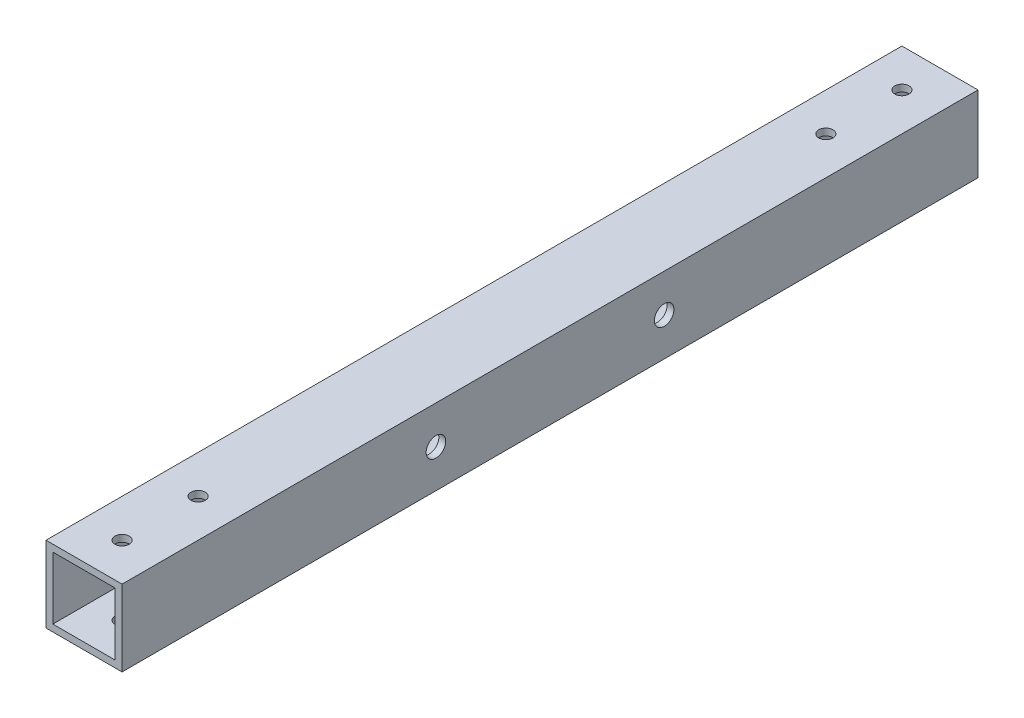
SolidWorks part; units mm, degrees
ref_plane "Front Plane" through (0, 0, 0) normal (0, 0, 1) x (1, 0, 0)
ref_plane "Top Plane" through (0, 0, 0) normal (0, 1, 0) x (1, 0, 0)
ref_plane "Right Plane" through (0, 0, 0) normal (1, 0, 0) x (0, 0, -1)
sketch "Sketch1" plane through (0, 0, 0) normal (0, 0, 1) x (1, 0, 0)
  line L0 (10.414, 10.414) -> (-10.414, 10.414)
  line L1 (12.7, -12.7) -> (-12.7, -12.7)
  line L2 (12.7, -12.7) -> (12.7, 12.7)
  line L3 (12.7, 12.7) -> (-12.7, 12.7)
  line L4 (-12.7, -12.7) -> (-12.7, 12.7)
  line L5 (12.7, -12.7) -> (-12.7, 12.7) construction
  line L6 (12.7, 12.7) -> (-12.7, -12.7) construction
  line L7 (-10.414, -10.414) -> (-10.414, 10.414)
  line L8 (10.414, -10.414) -> (-10.414, -10.414)
  line L9 (10.414, -10.414) -> (10.414, 10.414)
  point P0 (0, 0)
  dimension "D1" = 25.4
  dimension "D2" = 25.4
  dimension "D3" = 2.286
extrude "Boss-Extrude1" add sketch "Sketch1" along normal blind 285.75
hole_wizard "3/16 (0.1875) Diameter Hole7" positions "Sketch3" profile "Sketch2" hole size "3/16" standard "ANSI Inch" end condition through all
sketch "Sketch3" plane through (0, 12.7, 0) normal (0, 1, 0) x (1, 0, 0)
  line L0 (12.7, 0) -> (-12.7, 0) construction
  line L1 (12.7, -285.75) -> (-12.7, -285.75) construction
  point P0 (0, -273.05)
  point P2 (0, -247.65)
  point P3 (0, -12.7)
  point P5 (0, -38.1)
  dimension "D1" = 12.7
  dimension "D2" = 38.1
  dimension "D3" = 12.7
  dimension "D4" = 38.1
sketch "Sketch2" plane through (0, 12.7, 273.05) normal (1, 0, 0) x (0, 0, 1)
  line L0 (0, 0) -> (0, 25.4)
  line L1 (0, 25.4) -> (2.3812, 25.4)
  line L2 (2.3812, 25.4) -> (2.3812, 0)
  line L5 (2.3812, 0) -> (0, 0)
  line L11 (0, -6.35) -> (0, 107.95) construction
  dimension "Thru Hole Dia." = 4.7625
  dimension "Thru Hole Depth" = 25.4
hole_wizard " (0.257) Diameter Hole2" [suppressed] positions "Sketch11" profile "Sketch10" hole size "3/16" standard "ANSI Inch"
sketch "Sketch11" plane through (-12.7, 0, 0) normal (-1, 0, 0) x (0, 0, 1)
  line L0 (0, 0) -> (457.2, 0) construction
  line L1 (0, 12.7) -> (0, -12.7) construction
  line L2 (457.2, 12.7) -> (457.2, -12.7) construction
  line L3 (228.6, 12.7) -> (228.6, -12.7) construction
  line L4 (457.2, 12.7) -> (0, 12.7) construction
  line L5 (457.2, -12.7) -> (0, -12.7) construction
  point P0 (203.2, 0)
  point P2 (254, 0)
  dimension "D1" = 50.8
  dimension "D2" = 25.4
sketch "Sketch10" plane through (-12.7, 0, 203.2) normal (0, 1, 0) x (0, 0, 1)
  line L0 (0, 0) -> (0, 2.286)
  line L1 (0, 2.286) -> (3.2639, 2.286)
  line L2 (3.2639, 2.286) -> (3.2639, 0)
  line L5 (3.2639, 0) -> (0, 0)
  line L11 (0, -6.35) -> (0, 107.95) construction
  dimension "Thru Hole Dia." = 4.7625
  dimension "Thru Hole Depth" = 25.4
hole_wizard "F (0.257) Diameter Hole1" positions "Sketch13" profile "Sketch12" hole size "F" standard "ANSI Inch" end condition through all
sketch "Sketch13" plane through (12.7, 0, 0) normal (1, 0, 0) x (0, 0, -1)
  line L0 (-142.875, 12.7) -> (-142.875, -12.7) construction
  line L1 (-285.75, 12.7) -> (0, 12.7) construction
  line L2 (-285.75, -12.7) -> (0, -12.7) construction
  point P8 (-180.975, 0)
  point P10 (-104.775, 0)
  dimension "D1" = 38.1
  dimension "D2" = 38.1
sketch "Sketch12" plane through (12.7, 0, 180.975) normal (0, 1, 0) x (0, 0, -1)
  line L0 (0, 0) -> (0, 25.4)
  line L1 (0, 25.4) -> (3.2639, 25.4)
  line L2 (3.2639, 25.4) -> (3.2639, 0)
  line L5 (3.2639, 0) -> (0, 0)
  line L11 (0, -6.35) -> (0, 107.95) construction
  dimension "Thru Hole Dia." = 6.5278
  dimension "Thru Hole Depth" = 25.4
hole_wizard "3/16 (0.1875) Diameter Hole5" [suppressed] positions "Sketch16" profile "Sketch15" hole size "3/16" standard "ANSI Inch"
sketch "Sketch16" plane through (12.7, 0, 0) normal (1, 0, 0) x (0, 0, -1)
  line L0 (-247.65, 0) -> (0, 0) construction
  line L1 (-247.65, -12.7) -> (-247.65, 12.7) construction
  line L2 (0, -12.7) -> (0, 12.7) construction
  point P8 (-234.95, 0)
  point P10 (-209.55, 0)
  dimension "D1" = 25.4
  dimension "D2" = 12.7
sketch "Sketch15" plane through (12.7, 0, 234.95) normal (0, 1, 0) x (0, 0, -1)
  line L0 (0, 0) -> (0, 25.4)
  line L1 (0, 25.4) -> (2.3812, 25.4)
  line L2 (2.3812, 25.4) -> (2.3812, 0)
  line L5 (2.3812, 0) -> (0, 0)
  line L11 (0, -6.35) -> (0, 107.95) construction
  dimension "Thru Hole Dia." = 4.7625
  dimension "Thru Hole Depth" = 25.4
sketch "Sketch17" [suppressed] plane through (0, 12.7, 0) normal (0, 1, 0) x (1, 0, 0)
  line L4 (12.7, 0) -> (-12.7, 0)
  line L5 (-12.7, 0) -> (-12.7, -247.65)
  line L6 (-12.7, -247.65) -> (12.7, -247.65)
  line L7 (12.7, -247.65) -> (12.7, 0)
  line L8 (12.7, 0) -> (-12.7, 0)
  line L9 (-12.7, 0) -> (-12.7, -247.65)
  line L10 (-12.7, -247.65) -> (12.7, -247.65)
  line L11 (12.7, -247.65) -> (12.7, 0)
  circle A0 centre (0, -234.95) radius 2.3813 construction
  circle A1 centre (0, -234.95) radius 2.3812
  circle A2 centre (0, -234.95) radius 2.3813
  circle A3 centre (0, -209.55) radius 2.3812
  dimension "D1" = 0
extrude "Boss-Extrude2" [suppressed] add sketch "Sketch17" against normal blind 2.286
sketch "Sketch18" [suppressed] plane through (0, 0, 247.65) normal (0, 0, 1) x (1, 0, 0)
  line L0 (-12.7, 0) -> (12.7, 0) construction
  line L1 (-12.7, 12.7) -> (-12.7, -12.7) construction
  line L2 (12.7, -12.7) -> (12.7, 12.7) construction
ref_plane "Plane1" [suppressed] through (0, 0, 0) normal (0, 1, 0) x (1, 0, 0)
mirror "Mirror1" [suppressed] about plane through (0, 0, 0) normal (0, 1, 0)
sketch "Sketch19" [suppressed] plane through (-10.414, 0, 0) normal (1, 0, 0) x (0, 0, -1)
  circle A0 centre (-234.95, 0) radius 2.3813
  circle A1 centre (-209.55, 0) radius 2.3813
extrude "Boss-Extrude3" [suppressed] add sketch "Sketch19" against normal blind 2.286
hole_wizard "3/16 (0.1875) Diameter Hole8" [suppressed] positions "Sketch21" profile "Sketch20" hole size "3/16" standard "ANSI Inch"
sketch "Sketch21" plane through (0, 12.7, 0) normal (0, 1, 0) x (1, 0, 0)
  line L0 (-12.7, -142.875) -> (12.7, -142.875) construction
  line L1 (-12.7, -285.75) -> (-12.7, 0) construction
  line L2 (12.7, -285.75) -> (12.7, 0) construction
  line L3 (0, -285.75) -> (0, 0) construction
  line L4 (12.7, -285.75) -> (-12.7, -285.75) construction
  point P13 (0, -95.25)
  point P18 (0, -69.85)
  point P21 (0, -190.5)
  point P22 (0, -215.9)
  dimension "D1" = 47.625
  dimension "D2" = 25.4
sketch "Sketch20" plane through (0, 12.7, 95.25) normal (1, 0, 0) x (0, 0, 1)
  line L0 (0, 0) -> (0, 25.4)
  line L1 (0, 25.4) -> (2.3812, 25.4)
  line L2 (2.3812, 25.4) -> (2.3812, 0)
  line L5 (2.3812, 0) -> (0, 0)
  line L11 (0, -6.35) -> (0, 107.95) construction
  dimension "Thru Hole Dia." = 4.7625
  dimension "Thru Hole Depth" = 25.4
hole_wizard "3/16 (0.1875) Diameter Hole9" [suppressed] positions "Sketch23" profile "Sketch22" hole size "3/16" standard "ANSI Inch"
sketch "Sketch23" plane through (0, 12.7, 0) normal (0, 1, 0) x (1, 0, 0)
  line L0 (0, -285.75) -> (0, 0) construction
  line L1 (12.7, -285.75) -> (-12.7, -285.75) construction
  line L2 (-12.7, -142.875) -> (12.7, -142.875) construction
  line L3 (-12.7, -285.75) -> (-12.7, 0) construction
  line L4 (12.7, -285.75) -> (12.7, 0) construction
  point P13 (0, -82.55)
  point P18 (0, -57.15)
  point P22 (0, -228.6)
  point P23 (0, -203.2)
  dimension "D1" = 60.325
  dimension "D2" = 25.4
sketch "Sketch22" plane through (0, 12.7, 82.55) normal (1, 0, 0) x (0, 0, 1)
  line L0 (0, 0) -> (0, 25.4)
  line L1 (0, 25.4) -> (2.3812, 25.4)
  line L2 (2.3812, 25.4) -> (2.3812, 0)
  line L5 (2.3812, 0) -> (0, 0)
  line L11 (0, -6.35) -> (0, 107.95) construction
  dimension "Thru Hole Dia." = 4.7625
  dimension "Thru Hole Depth" = 25.4
hole_wizard "3/16 (0.1875) Diameter Hole10" [suppressed] positions "Sketch25" profile "Sketch24" hole size "3/16" standard "ANSI Inch"
sketch "Sketch25" plane through (0, 12.7, 0) normal (0, 1, 0) x (1, 0, 0)
  line L0 (0, -457.2) -> (0, 0) construction
  line L1 (12.7, -457.2) -> (-12.7, -457.2) construction
  circle A0 centre (0, -38.1) radius 2.3812 construction
  circle A1 centre (0, -419.1) radius 2.3813 construction
  point P8 (0, -63.5)
  point P13 (0, -393.7)
  dimension "D1" = 25.4
  dimension "D2" = 25.4
sketch "Sketch24" plane through (0, 12.7, 63.5) normal (1, 0, 0) x (0, 0, 1)
  line L0 (0, 0) -> (0, 25.4)
  line L1 (0, 25.4) -> (2.3812, 25.4)
  line L2 (2.3812, 25.4) -> (2.3812, 0)
  line L5 (2.3812, 0) -> (0, 0)
  line L11 (0, -6.35) -> (0, 107.95) construction
  dimension "Thru Hole Dia." = 4.7625
  dimension "Thru Hole Depth" = 25.4
hole_wizard "3/16 (0.1875) Diameter Hole11" [suppressed] positions "Sketch27" profile "Sketch26" hole size "3/16" standard "ANSI Inch"
sketch "Sketch27" plane through (0, 12.7, 0) normal (0, 1, 0) x (1, 0, 0)
  line L0 (12.7, -457.2) -> (-12.7, -457.2) construction
  point P0 (0, -168.275)
  point P5 (0, -142.875)
  point P7 (0, -193.675)
  dimension "D1" = 288.925
  dimension "D2" = 25.4
  dimension "D3" = 25.4
sketch "Sketch26" plane through (0, 12.7, 168.275) normal (1, 0, 0) x (0, 0, 1)
  line L0 (0, 0) -> (0, 25.4)
  line L1 (0, 25.4) -> (2.3812, 25.4)
  line L2 (2.3812, 25.4) -> (2.3812, 0)
  line L5 (2.3812, 0) -> (0, 0)
  line L11 (0, -6.35) -> (0, 107.95) construction
  dimension "Thru Hole Dia." = 4.7625
  dimension "Thru Hole Depth" = 25.4
